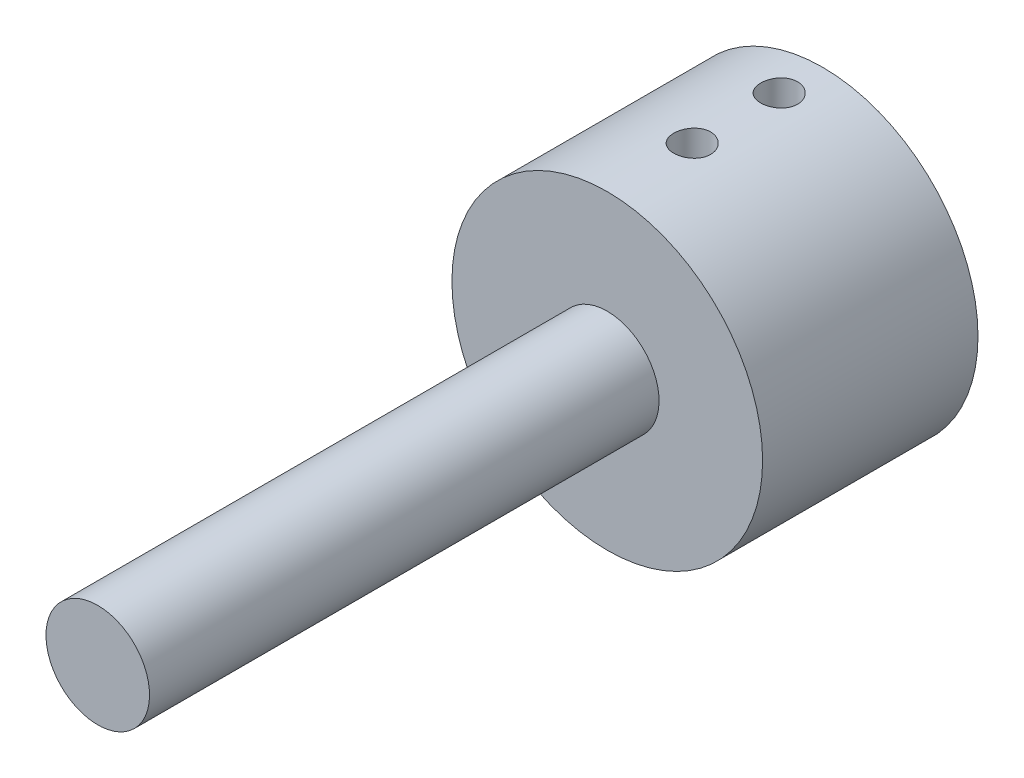
SolidWorks part; units mm, degrees
material "6061 Alloy"
ref_plane "Front Plane" through (0, 0, 0) normal (0, 0, 1) x (1, 0, 0)
ref_plane "Top Plane" through (0, 0, 0) normal (0, 1, 0) x (1, 0, 0)
ref_plane "Right Plane" through (0, 0, 0) normal (1, 0, 0) x (0, 0, -1)
sketch "Sketch" plane through (0, 0, 0) normal (1, 0, 0) x (0, 0, -1)
  line L0 (0, 0) -> (0, 3.175)
  line L1 (0, 3.175) -> (31.242, 3.175)
  line L2 (31.242, 3.175) -> (31.242, 9.525)
  line L3 (31.242, 9.525) -> (44.45, 9.525)
  line L4 (44.45, 9.525) -> (44.45, 6.35)
  line L5 (44.45, 6.35) -> (33.782, 6.35)
  line L6 (33.782, 6.35) -> (33.782, 0)
  line L7 (33.782, 0) -> (0, 0)
  dimension "D1" = 3.175
  dimension "D2" = 6.35
  dimension "D3" = 9.525
  dimension "D4" = 10.668
  dimension "D5" = 13.208
  dimension "D6" = 44.45
revolve "Shaft" add sketch "Sketch" angle 360 about L7
ref_plane "Set Screw Reference Plane" through (0, 9.525, 0) normal (0, 1, 0) x (1, 0, 0)
hole_wizard "#4-40 Tapped Hole1" positions "Sketch3" profile "Sketch2" tap size "#4-40" standard "ANSI Inch"
sketch "Sketch3" plane through (0, 9.525, 0) normal (0, 1, 0) x (1, 0, 0)
  line L0 (0, 31.242) -> (0, 44.45) construction
  line L1 (-3.175, 31.242) -> (3.175, 31.242) construction
  line L2 (6.35, 44.45) -> (-6.35, 44.45) construction
  line L3 (9.525, 44.45) -> (-9.525, 44.45) construction
  point P8 (0, 36.449)
  point P10 (0, 41.783)
  dimension "D1" = 2.667
  dimension "D2" = 8.001
sketch "Sketch2" plane through (0, 9.525, -36.449) normal (1, 0, 0) x (0, 0, 1)
  line L0 (0, 0) -> (0, 3.175)
  line L1 (0, 3.175) -> (1.1303, 3.175)
  line L2 (1.1303, 3.175) -> (1.1303, 0)
  line L5 (1.1303, 0) -> (0, 0)
  line L11 (0, -6.35) -> (0, 107.95) construction
  dimension "Thru Tap Drill Dia." = 2.2606
  dimension "Thru Tap Drill Depth" = 3.175
cosmetic thread "Hole Thread1" parameters "D2"=2.8448
cosmetic thread "Hole Thread2" parameters "D2"=2.8448
